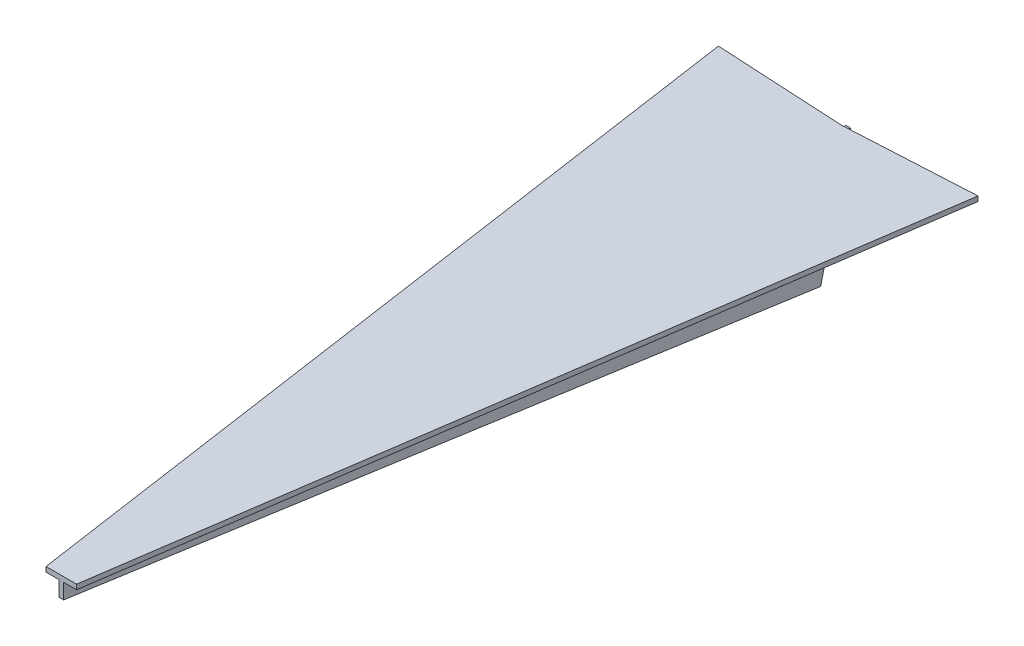
SolidWorks part; units mm, degrees
ref_plane "正面" through (0, 0, 0) normal (0, 0, 1) x (1, 0, 0)
ref_plane "平面" through (0, 0, 0) normal (0, 1, 0) x (1, 0, 0)
ref_plane "右側面" through (0, 0, 0) normal (1, 0, 0) x (0, 0, -1)
sketch "ｽｹｯﾁ1" plane through (0, 0, 0) normal (0, 1, 0) x (1, 0, 0)
  line L0 (0, 0) -> (0, 255) construction
  line L1 (0, 255) -> (42.4382, 257.2905)
  line L2 (42.4382, 257.2905) -> (5, 0)
  line L3 (5, 0) -> (-5, 0)
  line L4 (-42.4382, 257.2905) -> (-5, 0)
  line L5 (0, 255) -> (-42.4382, 257.2905)
  dimension "D1" = 255
  dimension "D2" = 42.5
  dimension "D3" = 5
  dimension "D4" = 260
extrude "ﾎﾞｽ - 押し出し1" add sketch "ｽｹｯﾁ1" along normal blind 1.6
sketch "ｽｹｯﾁ2" plane through (0, 0, 0) normal (1, 0, 0) x (0, 0, -1)
  line L0 (0, 0) -> (0, -5)
  line L1 (0, -5) -> (247.5379, -40)
  line L2 (247.5379, -40) -> (257.2905, 0)
  line L3 (0, 0) -> (257.2905, 0)
  dimension "D1" = 40
  dimension "D2" = 250
  dimension "D3" = 5
extrude "ﾎﾞｽ - 押し出し2" add sketch "ｽｹｯﾁ2" along normal mid plane 1.5
